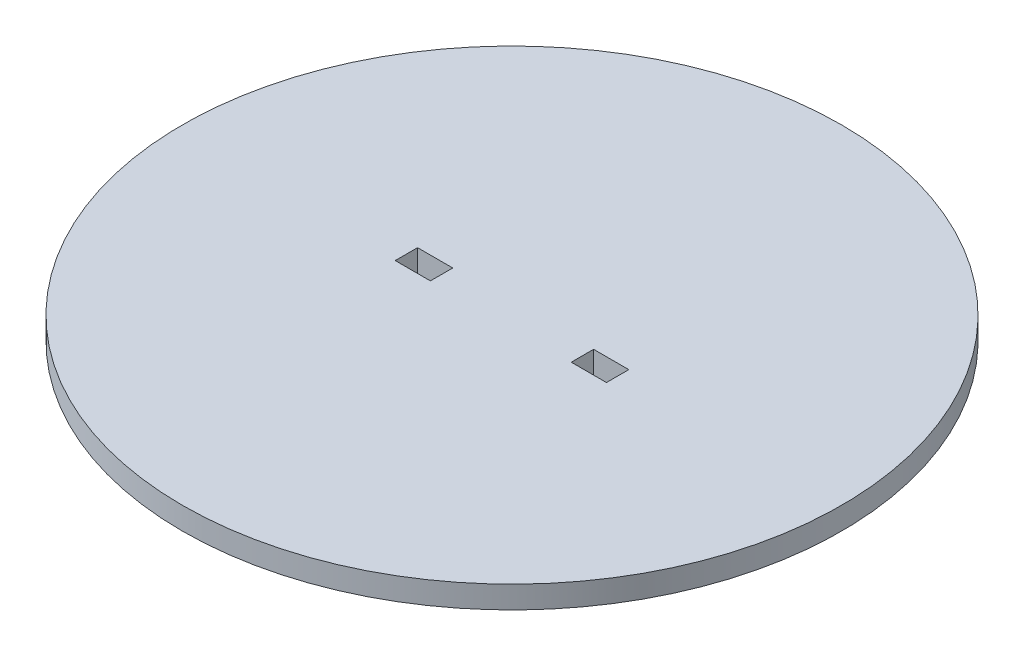
SolidWorks part; units mm, degrees
ref_plane "Front Plane" through (0, 0, 0) normal (0, 0, 1) x (1, 0, 0)
ref_plane "Top Plane" through (0, 0, 0) normal (0, 1, 0) x (1, 0, 0)
ref_plane "Right Plane" through (0, 0, 0) normal (1, 0, 0) x (0, 0, -1)
sketch "Sketch1" plane through (0, 0, 0) normal (0, 1, 0) x (1, 0, 0)
  line L0 (-10, 0) -> (10, 0) construction
  line L1 (-15, -1.5875) -> (-10, -1.5875)
  line L2 (-15, -1.5875) -> (-15, 1.5875)
  line L3 (-15, 1.5875) -> (-10, 1.5875)
  line L4 (-10, -1.5875) -> (-10, 1.5875)
  line L5 (-15, -1.5875) -> (-10, 1.5875) construction
  line L6 (-15, 1.5875) -> (-10, -1.5875) construction
  line L7 (10, -1.5875) -> (15, -1.5875)
  line L8 (10, -1.5875) -> (10, 1.5875)
  line L9 (10, 1.5875) -> (15, 1.5875)
  line L10 (15, -1.5875) -> (15, 1.5875)
  line L11 (10, -1.5875) -> (15, 1.5875) construction
  line L12 (10, 1.5875) -> (15, -1.5875) construction
  circle A0 centre (0, 0) radius 46.8
  point P3 (-12.5, 0)
  point P8 (12.5, 0)
  point P15 (0, 0)
  dimension "D1" = 93.6
  dimension "D2" = 5
  dimension "D3" = 5
  dimension "D4" = 3.175
  dimension "D5" = 3.175
  dimension "D6" = 20
extrude "Boss-Extrude1" add sketch "Sketch1" along normal blind 3.175
